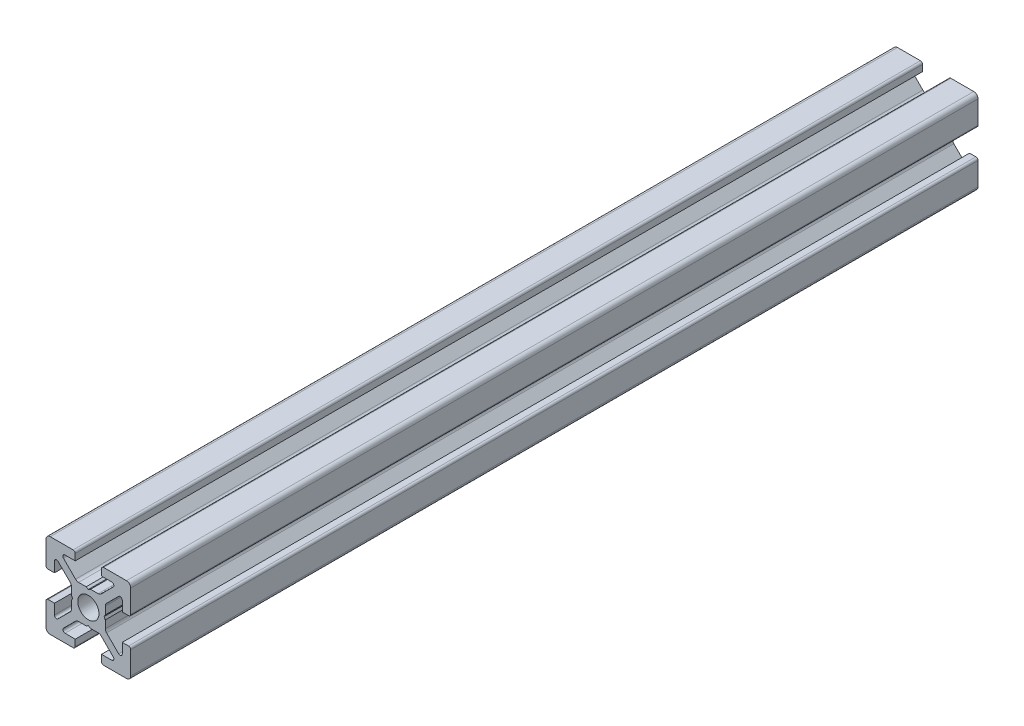
SolidWorks part; units mm, degrees
ref_plane "前视基准面" through (0, 0, 0) normal (0, 0, 1) x (1, 0, 0)
ref_plane "上视基准面" through (0, 0, 0) normal (0, 1, 0) x (1, 0, 0)
ref_plane "右视基准面" through (0, 0, 0) normal (1, 0, 0) x (0, 0, -1)
sketch "草图1" plane through (0, 0, 0) normal (0, 0, 1) x (1, 0, 0)
  line L0 (16.4868, 27.1233) -> (19.3403, 24.2698)
  line L1 (20.1939, 24.6233) -> (20.1939, 27.0434)
  line L2 (20.1939, 27.0434) -> (21.6939, 27.0434)
  line L3 (15.8939, 30.1434) -> (16.1939, 29.6238)
  line L4 (12.1939, 33.8434) -> (12.7135, 34.1434)
  line L5 (22.1939, 26.5434) -> (22.1939, 21.1434)
  line L6 (21.1939, 20.1434) -> (15.7939, 20.1434)
  line L7 (12.1939, 33.8434) -> (11.6743, 34.1434)
  line L8 (12.7135, 34.1434) -> (14.5069, 34.1434)
  line L9 (15.2939, 20.6434) -> (15.2939, 22.1434)
  line L10 (15.2939, 22.1434) -> (17.714, 22.1434)
  line L11 (18.0675, 22.997) -> (15.214, 25.8506)
  line L12 (14.5069, 26.1434) -> (12.7135, 26.1434)
  line L13 (9.1738, 25.8506) -> (6.3202, 22.997)
  line L14 (6.6738, 22.1434) -> (9.0939, 22.1434)
  line L15 (9.0939, 22.1434) -> (9.0939, 20.6434)
  line L16 (15.8939, 30.1434) -> (16.1939, 30.6631)
  line L17 (12.1939, 26.4434) -> (11.6743, 26.1434)
  line L18 (8.5939, 20.1434) -> (3.1939, 20.1434)
  line L19 (2.1939, 21.1434) -> (2.1939, 26.5434)
  line L20 (12.1939, 26.4434) -> (12.7135, 26.1434)
  line L21 (8.4939, 30.1434) -> (8.1939, 30.6631)
  line L22 (2.6939, 27.0434) -> (4.1939, 27.0434)
  line L23 (4.1939, 27.0434) -> (4.1939, 24.6233)
  line L24 (5.0474, 24.2698) -> (7.901, 27.1233)
  line L25 (8.1939, 27.8305) -> (8.1939, 29.6238)
  line L26 (7.901, 33.1635) -> (5.0474, 36.0171)
  line L27 (4.1939, 35.6635) -> (4.1939, 33.2434)
  line L28 (4.1939, 33.2434) -> (2.6939, 33.2434)
  line L29 (8.4939, 30.1434) -> (8.1939, 29.6238)
  line L30 (16.1939, 29.6238) -> (16.1939, 27.8305)
  line L31 (2.1939, 33.7434) -> (2.1939, 39.1434)
  line L32 (3.1939, 40.1434) -> (8.5939, 40.1434)
  line L33 (11.6743, 26.1434) -> (9.8809, 26.1434)
  line L34 (8.1939, 30.6631) -> (8.1939, 32.4564)
  line L35 (9.0939, 39.6434) -> (9.0939, 38.1434)
  line L36 (9.0939, 38.1434) -> (6.6738, 38.1434)
  line L37 (6.3202, 37.2899) -> (9.1738, 34.4363)
  line L38 (9.8809, 34.1434) -> (11.6743, 34.1434)
  line L39 (15.214, 34.4363) -> (18.0675, 37.2899)
  line L40 (17.714, 38.1434) -> (15.2939, 38.1434)
  line L41 (15.2939, 38.1434) -> (15.2939, 39.6434)
  line L44 (15.7939, 40.1434) -> (21.1939, 40.1434)
  line L45 (22.1939, 39.1434) -> (22.1939, 33.7434)
  line L48 (21.6939, 33.2434) -> (20.1939, 33.2434)
  line L49 (20.1939, 33.2434) -> (20.1939, 35.6635)
  line L50 (19.3403, 36.0171) -> (16.4868, 33.1635)
  line L51 (16.1939, 32.4564) -> (16.1939, 30.6631)
  circle A0 centre (12.1939, 30.1434) radius 2.5
  arc A1 (16.1939, 27.8305) -> (16.4868, 27.1233) centre (17.1939, 27.8305) ccw
  arc A2 (19.3403, 24.2698) -> (20.1939, 24.6233) centre (19.6939, 24.6233) ccw
  arc A3 (21.1939, 20.1434) -> (22.1939, 21.1434) centre (21.1939, 21.1434) ccw
  arc A4 (17.714, 22.1434) -> (18.0675, 22.997) centre (17.714, 22.6434) ccw
  arc A5 (15.214, 25.8506) -> (14.5069, 26.1434) centre (14.5069, 25.1434) ccw
  arc A6 (9.8809, 26.1434) -> (9.1738, 25.8506) centre (9.8809, 25.1434) ccw
  arc A7 (6.3202, 22.997) -> (6.6738, 22.1434) centre (6.6738, 22.6434) ccw
  arc A8 (2.1939, 21.1434) -> (3.1939, 20.1434) centre (3.1939, 21.1434) ccw
  arc A9 (4.1939, 24.6233) -> (5.0474, 24.2698) centre (4.6939, 24.6233) ccw
  arc A10 (7.901, 27.1233) -> (8.1939, 27.8305) centre (7.1939, 27.8305) ccw
  arc A11 (8.1939, 32.4564) -> (7.901, 33.1635) centre (7.1939, 32.4564) ccw
  arc A12 (5.0474, 36.0171) -> (4.1939, 35.6635) centre (4.6939, 35.6635) ccw
  arc A13 (3.1939, 40.1434) -> (2.1939, 39.1434) centre (3.1939, 39.1434) ccw
  arc A14 (6.6738, 38.1434) -> (6.3202, 37.2899) centre (6.6738, 37.6434) ccw
  arc A15 (9.1738, 34.4363) -> (9.8809, 34.1434) centre (9.8809, 35.1434) ccw
  arc A16 (14.5069, 34.1434) -> (15.214, 34.4363) centre (14.5069, 35.1434) ccw
  arc A17 (18.0675, 37.2899) -> (17.714, 38.1434) centre (17.714, 37.6434) ccw
  arc A18 (22.1939, 39.1434) -> (21.1939, 40.1434) centre (21.1939, 39.1434) ccw
  arc A19 (20.1939, 35.6635) -> (19.3403, 36.0171) centre (19.6939, 35.6635) ccw
  arc A20 (16.4868, 33.1635) -> (16.1939, 32.4564) centre (17.1939, 32.4564) ccw
  arc A21 (15.7939, 20.1434) -> (15.2939, 20.6434) centre (15.7939, 20.6434) cw
  arc A22 (9.0939, 20.6434) -> (8.5939, 20.1434) centre (8.5939, 20.6434) cw
  arc A23 (2.1939, 26.5434) -> (2.6939, 27.0434) centre (2.6939, 26.5434) cw
  arc A24 (2.6939, 33.2434) -> (2.1939, 33.7434) centre (2.6939, 33.7434) cw
  arc A25 (22.1939, 26.5434) -> (21.6939, 27.0434) centre (21.6939, 26.5434) ccw
  arc A26 (21.6939, 33.2434) -> (22.1939, 33.7434) centre (21.6939, 33.7434) ccw
  arc A27 (15.7939, 40.1434) -> (15.2939, 39.6434) centre (15.7939, 39.6434) ccw
  arc A28 (9.0939, 39.6434) -> (8.5939, 40.1434) centre (8.5939, 39.6434) ccw
  dimension "D1" = 0.5
  dimension "D2" = 4
extrude "凸台-拉伸1" add sketch "草图1" along normal blind 200
